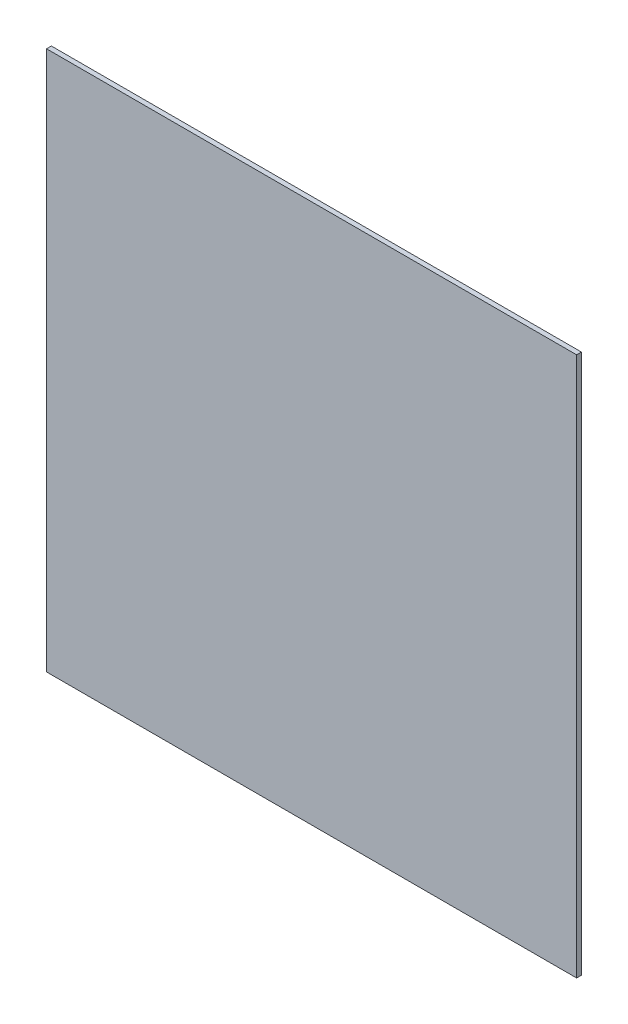
SolidWorks part; units mm, degrees
ref_plane "Front Plane" through (0, 0, 0) normal (0, 0, 1) x (1, 0, 0)
ref_plane "Top Plane" through (0, 0, 0) normal (0, 1, 0) x (1, 0, 0)
ref_plane "Right Plane" through (0, 0, 0) normal (1, 0, 0) x (0, 0, -1)
sketch "Sketch1" plane through (0, 0, 0) normal (0, 0, 1) x (1, 0, 0)
  line L1 (2750, -2800) -> (-2750, -2800)
  line L2 (2750, -2800) -> (2750, 2800)
  line L3 (2750, 2800) -> (-2750, 2800)
  line L4 (-2750, -2800) -> (-2750, 2800)
  line L5 (2750, -2800) -> (-2750, 2800) construction
  line L6 (2750, 2800) -> (-2750, -2800) construction
  point P0 (0, 0)
  dimension "D1" = 5600
  dimension "D2" = 5500
extrude "Boss-Extrude1" add sketch "Sketch1" along normal blind 50
sketch "Sketch2" plane through (0, 0, 0) normal (0, 0, -1) x (-1, 0, 0)
  line L1 (-1000, 2750) -> (-1000, -2750)
  line L2 (-2750, 2800) -> (2750, 2800) construction
  line L4 (-2750, -2800) -> (-2750, 2800) construction
  line L5 (-2700, 0) -> (2700, 0)
  line L6 (2700, -2750) -> (-2700, -2750)
  line L7 (2700, -2750) -> (2700, 2750)
  line L8 (2700, 2750) -> (-2700, 2750)
  line L9 (-2700, -2750) -> (-2700, 2750)
  line L10 (2700, -2750) -> (-2700, 2750) construction
  line L11 (2700, 2750) -> (-2700, -2750) construction
  line L12 (-2700, 1375) -> (2700, 1375)
  line L13 (-2700, -1375) -> (2700, -1375)
  line L14 (-625, 1000) -> (-1375, 1000)
  line L15 (-625, 1000) -> (-625, 1750)
  line L16 (-625, 1750) -> (-1375, 1750)
  line L17 (-1375, 1000) -> (-1375, 1750)
  line L18 (-625, 1000) -> (-1375, 1750) construction
  line L19 (-625, 1750) -> (-1375, 1000) construction
  line L21 (-625, -1750) -> (-1375, -1750)
  line L22 (-625, -1750) -> (-625, -1000)
  line L23 (-625, -1000) -> (-1375, -1000)
  line L24 (-1375, -1750) -> (-1375, -1000)
  line L25 (-625, -1750) -> (-1375, -1000) construction
  line L26 (-625, -1000) -> (-1375, -1750) construction
  point P8 (0, 0)
  point P16 (-1000, 1375)
  point P23 (-1000, -1375)
  dimension "D1" = 1700
  dimension "D2" = 50
  dimension "D3" = 50
  dimension "D4" = 5500
  dimension "D5" = 1375
  dimension "D6" = 750
  dimension "D7" = 750
  dimension "D8" = 1375
  dimension "D9" = 750
  dimension "D10" = 750
extrude "Cut-Extrude1" cut sketch "Sketch2" against normal blind 10 contours L17 L12 L1 L16 | L14 L15 L12 L1 | L17 L14 L1 L12 | L15 L16 L1 L12 | L24 L21 L1 L13 | L21 L22 L13 L1 | L22 L23 L1 L13 | L24 L13 L1 L23
